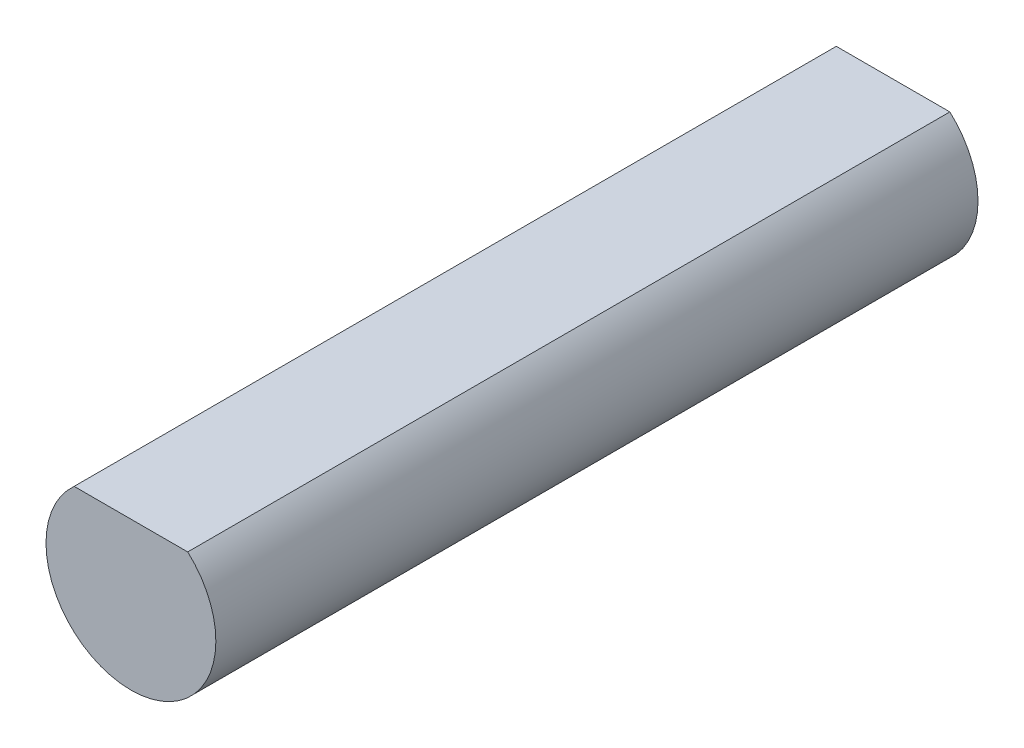
SolidWorks part; units mm, degrees
ref_plane "前视基准面" through (0, 0, 0) normal (0, 0, 1) x (1, 0, 0)
ref_plane "上视基准面" through (0, 0, 0) normal (0, 1, 0) x (1, 0, 0)
ref_plane "右视基准面" through (0, 0, 0) normal (1, 0, 0) x (0, 0, -1)
sketch "草图1" plane through (0, 0, 0) normal (0, 0, 1) x (1, 0, 0)
  circle A0 centre (0, 0) radius 3.9
  dimension "D1" = 7.8
extrude "凸台-拉伸1" add sketch "草图1" along normal blind 35
sketch "草图2" plane through (0, 0, 35) normal (0, 0, 1) x (1, 0, 0)
  line L1 (-5.3417, 6.8431) -> (4.3432, 6.8431)
  line L2 (-5.3417, 6.8431) -> (-5.3417, 2.9)
  line L3 (-5.3417, 2.9) -> (4.3432, 2.9)
  line L4 (4.3432, 6.8431) -> (4.3432, 2.9)
  dimension "D1" = 2.9
extrude "切除-拉伸1" cut sketch "草图2" against normal through all
